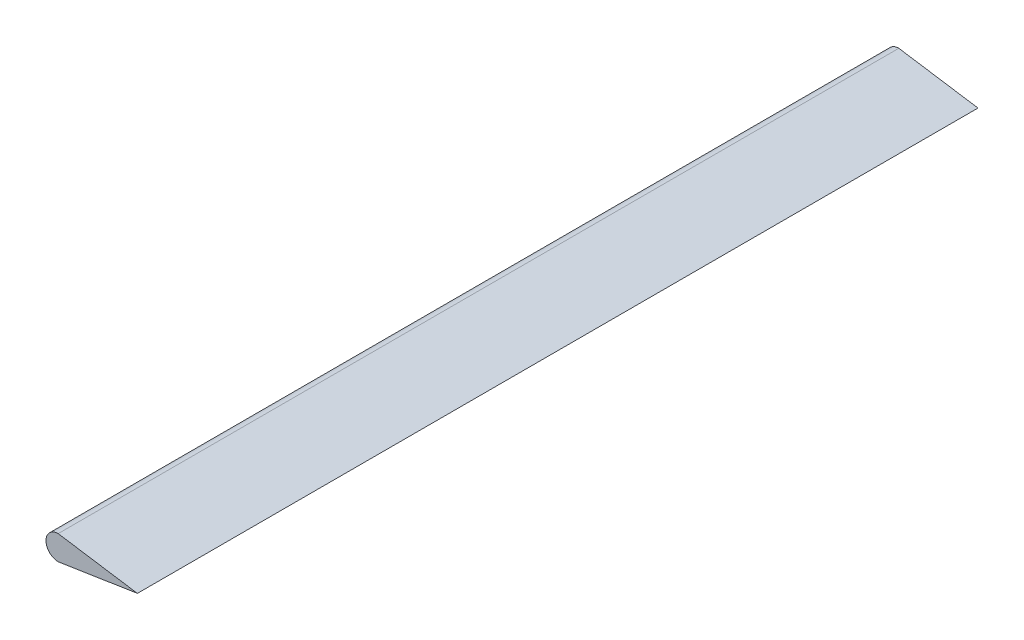
SolidWorks part; units mm, degrees
ref_plane "Front Plane" through (0, 0, 0) normal (0, 0, 1) x (1, 0, 0)
ref_plane "Top Plane" through (0, 0, 0) normal (0, 1, 0) x (1, 0, 0)
ref_plane "Right Plane" through (0, 0, 0) normal (1, 0, 0) x (0, 0, -1)
sketch "Sketch1" plane through (0, 0, 0) normal (0, 0, 1) x (1, 0, 0)
  line L0 (0, 0) -> (1500, 0) construction
  line L1 (200, 200) -> (1500, 0)
  line L2 (1500, 0) -> (200, -200)
  arc A0 (200, 200) -> (200, -200) centre (200, 0) ccw
  dimension "D2" = 400
  dimension "D1" = 1500
extrude "Boss-Extrude2" add sketch "Sketch1" along normal blind 13800 contours L1 L2 A0
